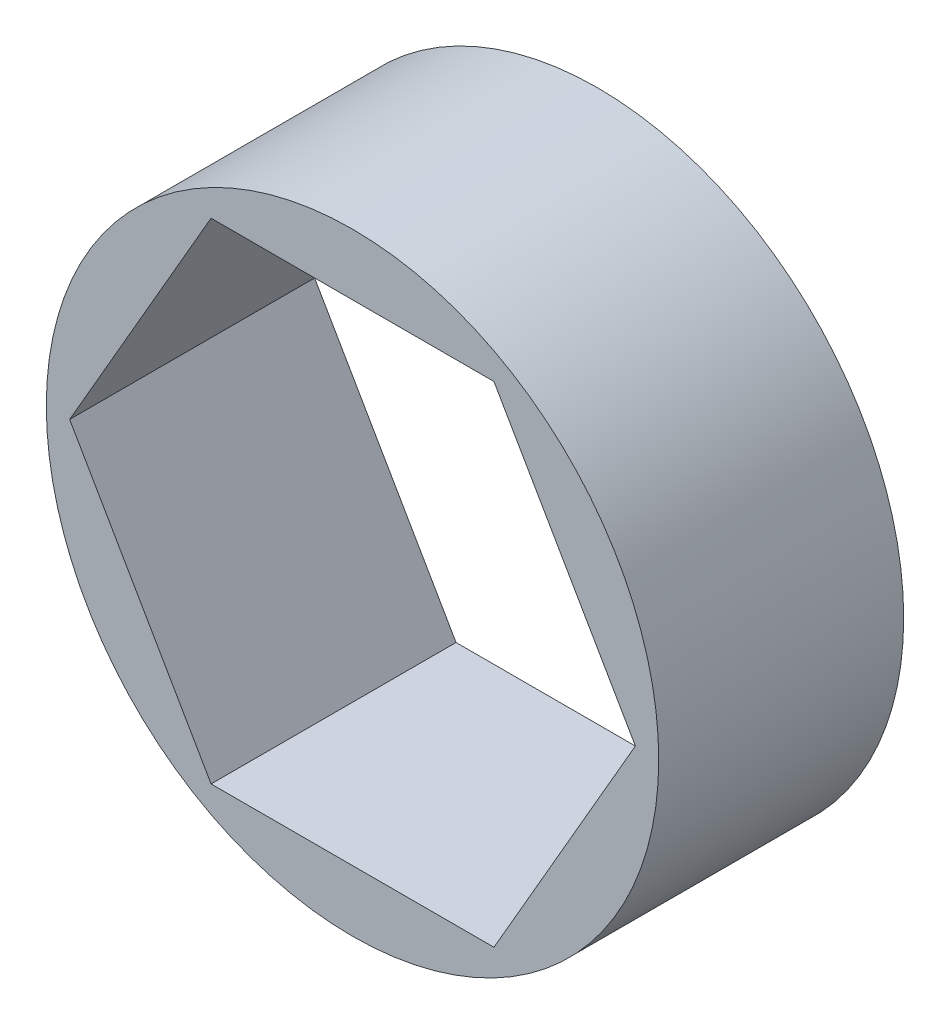
SolidWorks part; units mm, degrees
material "ABS"
ref_plane "Front Plane" through (0, 0, 0) normal (0, 0, 1) x (1, 0, 0)
ref_plane "Top Plane" through (0, 0, 0) normal (0, 1, 0) x (1, 0, 0)
ref_plane "Right Plane" through (0, 0, 0) normal (1, 0, 0) x (0, 0, -1)
sketch "Sketch1" plane through (0, 0, 0) normal (0, 0, 1) x (1, 0, 0)
  line L1 (-3.6662, -6.35) -> (3.6662, -6.35)
  line L2 (3.6662, -6.35) -> (7.3323, 0)
  line L3 (7.3323, 0) -> (3.6662, 6.35)
  line L4 (3.6662, 6.35) -> (-3.6662, 6.35)
  line L5 (-3.6662, 6.35) -> (-7.3323, 0)
  line L6 (-7.3323, 0) -> (-3.6662, -6.35)
  circle A0 centre (0, 0) radius 6.35 construction
  circle A1 centre (0, 0) radius 7.9375
  dimension "D1" = 12.7
  dimension "D2" = 15.875
extrude "Boss-Extrude1" add sketch "Sketch1" along normal blind 6.35
